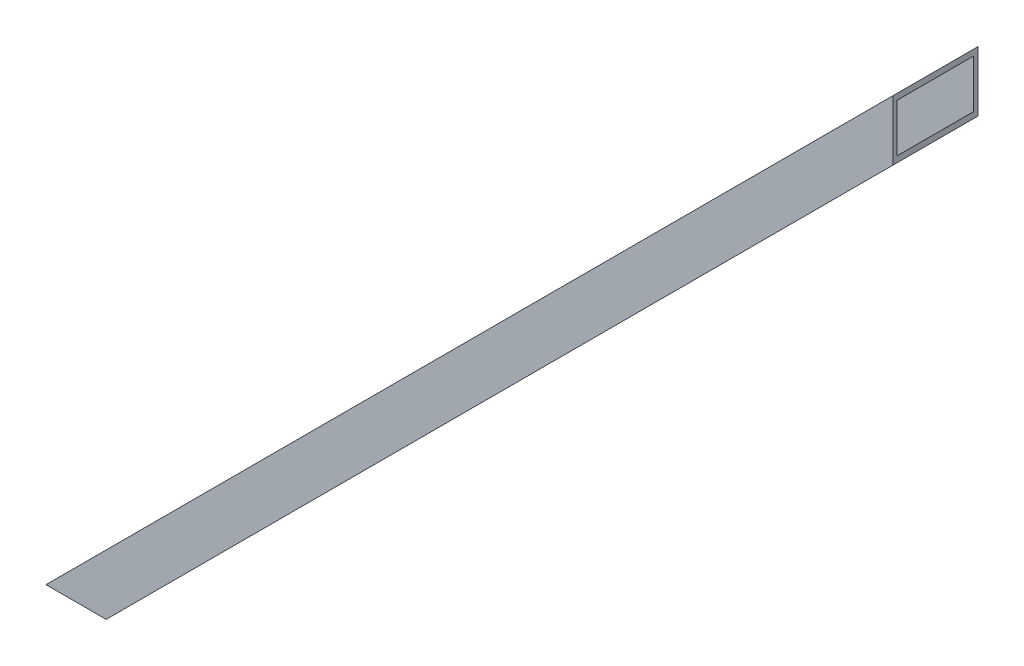
SolidWorks part; units mm, degrees
material "6061-T6 (SS)"
ref_plane "前视基准面" through (0, 0, 0) normal (0, 0, 1) x (1, 0, 0)
ref_plane "上视基准面" through (0, 0, 0) normal (0, 1, 0) x (1, 0, 0)
ref_plane "右视基准面" through (0, 0, 0) normal (1, 0, 0) x (0, 0, -1)
sketch "草图1" plane through (0, 0, 0) normal (0, 0, 1) x (1, 0, 0)
  line L0 (0, 0) -> (0, 20) construction
  line L1 (0, 0) -> (185, 0) construction
  line L2 (185, 0) -> (185, 200) construction
  line L3 (0, 20) -> (-14.1421, 20) construction
  line L4 (0, 20) -> (185, 205)
  line L5 (0, 20) -> (-14.1421, 20)
  line L6 (-14.1421, 20) -> (185, 219.1421)
  line L7 (185, 219.1421) -> (185, 205)
  dimension "D1" = 20
  dimension "D2" = 185
  dimension "D3" = 200
  dimension "D4" = 10
  dimension "D5" = 45
extrude "凸台-拉伸1" add sketch "草图1" along normal mid plane 20
ref_plane "基准面1" through (10, 10, 0) normal (-0.7071, -0.7071, 0) x (0, 0, -1)
sketch "草图2" plane through (10, 10, 0) normal (-0.7071, -0.7071, 0) x (0, 0, -1)
  line L0 (-9, -15.1421) -> (-9, -23.1421)
  line L1 (-9, -23.1421) -> (9, -23.1421)
  line L2 (9, -23.1421) -> (9, -15.1421)
  line L3 (9, -15.1421) -> (-9, -15.1421)
  line L4 (10, -24.1421) -> (10, -14.1421)
  line L5 (10, -14.1421) -> (-10, -14.1421)
  line L6 (-10, -14.1421) -> (-10, -24.1421)
  line L7 (-10, -24.1421) -> (10, -24.1421)
  line L8 (10, -24.1421) -> (10, -14.1421)
  line L9 (10, -14.1421) -> (-10, -14.1421)
  line L10 (-10, -14.1421) -> (-10, -24.1421)
  line L11 (-10, -24.1421) -> (10, -24.1421)
  dimension "D1" = 0
  dimension "D2" = 1
extrude "切除-拉伸1" cut sketch "草图2" against normal through all both and the other way through all contours L2 L3 L0 L1
sketch "草图3" plane through (-17.0711, 17.0711, 0) normal (-0.7071, 0.7071, 0) x (0.7071, 0.7071, 0)
  line L0 (285.7716, 0) -> (50.5611, 0) construction
  line L1 (285.7716, -10) -> (285.7716, 10) construction
  circle A0 centre (247.7716, 6) radius 1.6
  circle A1 centre (247.7716, -6) radius 1.6
  dimension "D1" = 12
  dimension "D2" = 3.2
  dimension "D3" = 38
extrude "切除-拉伸2" cut sketch "草图3" against normal through all
